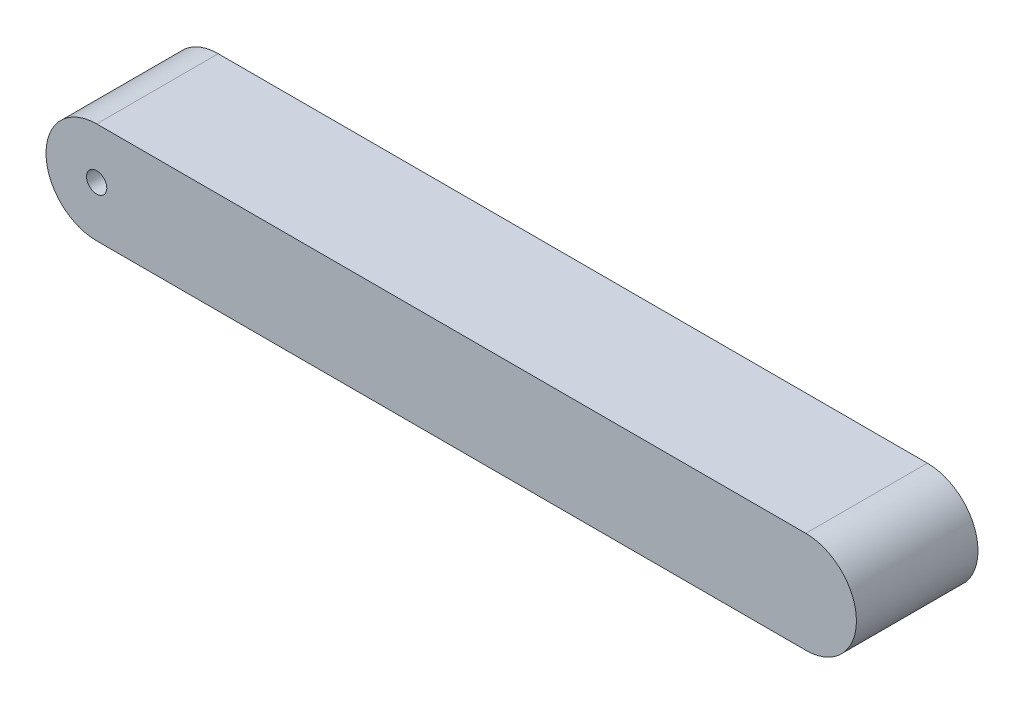
SolidWorks part; units mm, degrees
ref_plane "前视基准面" through (0, 0, 0) normal (0, 0, 1) x (1, 0, 0)
ref_plane "上视基准面" through (0, 0, 0) normal (0, 1, 0) x (1, 0, 0)
ref_plane "右视基准面" through (0, 0, 0) normal (1, 0, 0) x (0, 0, -1)
sketch "草图1" plane through (0, 0, 0) normal (0, 0, 1) x (1, 0, 0)
  line L1 (0, 0) -> (350, 0)
  line L2 (0, 0) -> (0, 50)
  line L3 (0, 50) -> (350, 50)
  line L4 (350, 0) -> (350, 50)
  circle A0 centre (0, 25) radius 25
  circle A1 centre (350, 25) radius 25
  circle A2 centre (0, 25) radius 5
  dimension "D3" = 10
  dimension "D1" = 350
  dimension "D2" = 50
extrude "凸台-拉伸1" add sketch "草图1" along normal blind 60 contours L2 A0 | L2 A0 | A1 L3 A0 L1 | L4 A1 | L4 A1
